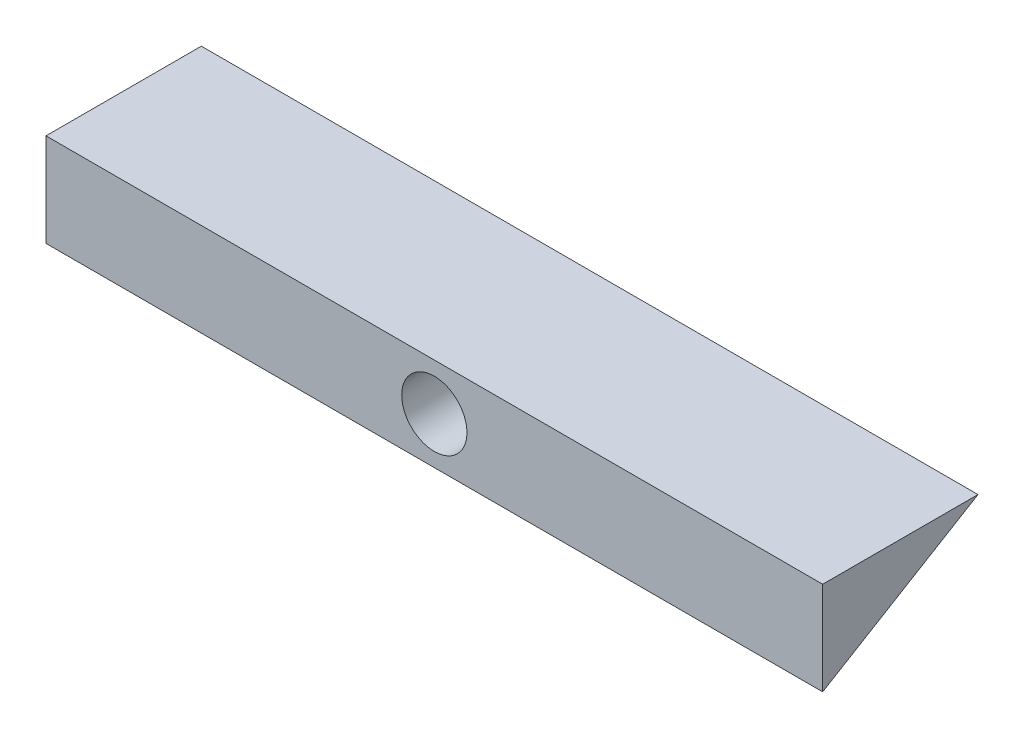
SolidWorks part; units mm, degrees
ref_plane "Front Plane" through (0, 0, 0) normal (0, 0, 1) x (1, 0, 0)
ref_plane "Top Plane" through (0, 0, 0) normal (0, 1, 0) x (1, 0, 0)
ref_plane "Right Plane" through (0, 0, 0) normal (1, 0, 0) x (0, 0, -1)
sketch "Sketch1" plane through (0, 0, 0) normal (1, 0, 0) x (0, 0, -1)
  line L0 (0, 0) -> (-5, 0)
  line L1 (-5, 0) -> (-5, -3)
  line L2 (-5, -3) -> (0, 0)
  dimension "D1" = 3
  dimension "D2" = 5
extrude "Boss-Extrude1" add sketch "Sketch1" along normal blind 25
sketch "Sketch2" plane through (0, 0, 5) normal (0, 0, 1) x (1, 0, 0)
  line L0 (25, -3) -> (0, -3) construction
  line L5 (25, 0) -> (0, 0) construction
  line L10 (10.5, 0) -> (14.5, 0)
  line L11 (10.5, 0) -> (10.5, -3)
  line L12 (10.5, -3) -> (14.5, -3)
  line L13 (14.5, 0) -> (14.5, -3)
  line L14 (25, 0) -> (25, -3) construction
  dimension "D1" = 10.5
  dimension "D3" = 4
extrude "Boss-Extrude2" add sketch "Sketch2" against normal blind 5
sketch "Sketch3" plane through (0, 0, 0) normal (0, 0, -1) x (-1, 0, 0)
  line L0 (-14.5, 0) -> (-10.5, 0) construction
  line L1 (-14.5, -3) -> (-14.5, 0) construction
  circle A0 centre (-12.5, -1.5) radius 1.05
  dimension "D3" = 2.1
  dimension "D1" = 1.5
  dimension "D2" = 2
extrude "Cut-Extrude1" cut sketch "Sketch3" against normal through all both and the other way through all
